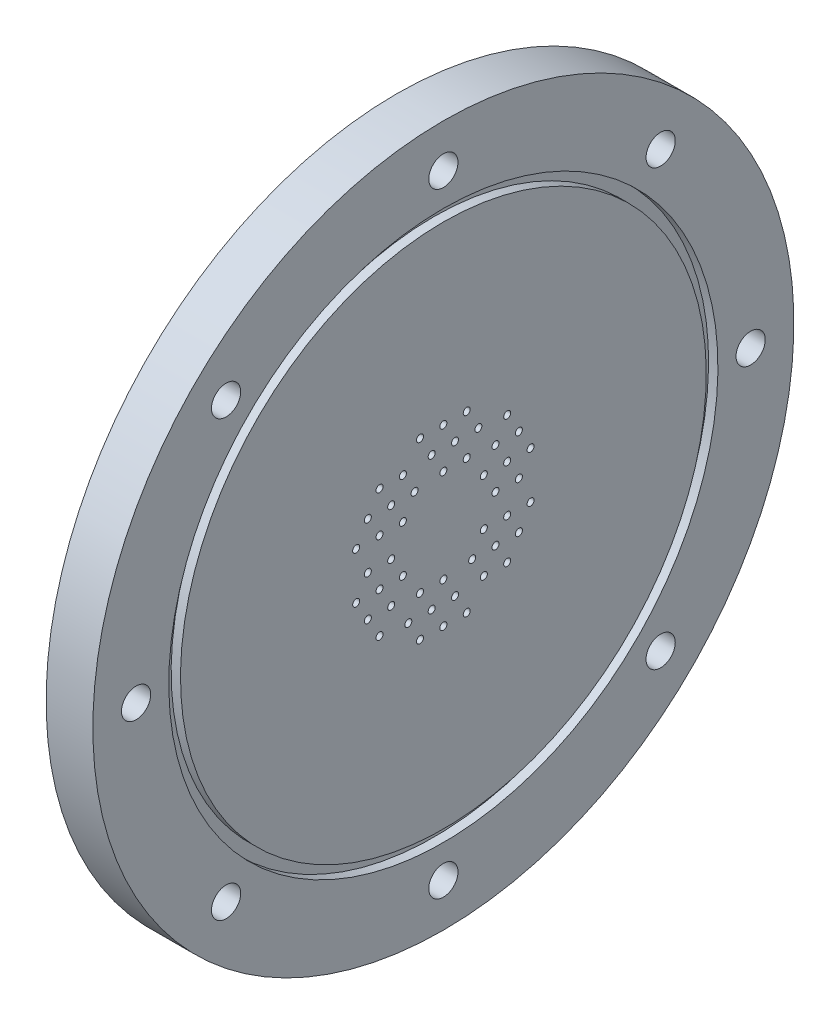
SolidWorks part; units mm, degrees
ref_plane "Front Plane" through (0, 0, 0) normal (0, 0, 1) x (1, 0, 0)
ref_plane "Top Plane" through (0, 0, 0) normal (0, 1, 0) x (1, 0, 0)
ref_plane "Right Plane" through (0, 0, 0) normal (1, 0, 0) x (0, 0, -1)
sketch "Sketch1" plane through (0, 0, 0) normal (0, 0, 1) x (1, 0, 0)
  line L0 (0, 0) -> (0, 48.26)
  line L1 (-2.54, 50.8) -> (-6.35, 50.8)
  line L2 (-6.35, 50.8) -> (-6.35, 76.2)
  line L3 (-6.35, 76.2) -> (3.81, 76.2)
  line L4 (3.81, 76.2) -> (3.81, 0)
  line L5 (3.81, 0) -> (0, 0)
  line L6 (-6.35, 50.8) -> (-6.35, 0) construction
  line L7 (-6.35, 0) -> (0, 0) construction
  arc A0 (0, 48.26) -> (-2.54, 50.8) centre (-2.54, 48.26) ccw
  dimension "Injector Plate Edge Curve" = 2.54
  dimension "Injector Plate Main Thickness" = 3.81
  dimension "Comp" = 152.4
  dimension "Injector Plate Boundry" = 25.4
  dimension "Injector Plate Manifold Height" = 6.35
revolve "Revolve1" add sketch "Sketch1" angle 360 about L7
sketch "Sketch2" plane through (3.81, 0, 0) normal (1, 0, 0) x (0, 0, -1)
  line L0 (0, 10.16) -> (5.08, 10.16) construction
  line L37 (5.08, 10.16) -> (2.54, 14.5594) construction
  line L38 (0, 10.16) -> (-2.54, 14.5594) construction
  line L39 (2.54, 14.5594) -> (0, 10.16) construction
  line L40 (-2.54, 14.5594) -> (2.54, 14.5594) construction
  line L41 (2.54, 14.5594) -> (7.62, 14.5594) construction
  line L42 (7.62, 14.5594) -> (5.08, 10.16) construction
  line L43 (2.54, 14.5594) -> (5.08, 18.9588) construction
  line L44 (5.08, 18.9588) -> (7.62, 14.5594) construction
  line L45 (-2.54, 14.5594) -> (0, 18.9588) construction
  line L46 (0, 18.9588) -> (2.54, 14.5594) construction
  line L47 (0, 18.9588) -> (5.08, 18.9588) construction
  line L48 (-2.54, 14.5594) -> (-5.08, 18.9588) construction
  line L49 (-5.08, 18.9588) -> (0, 18.9588) construction
  circle A3 centre (0, 10.16) radius 0.762
  circle A7 centre (-2.54, 14.5594) radius 0.762
  circle A8 centre (5.08, 10.16) radius 0.762
  circle A9 centre (-5.08, 18.9588) radius 0.762
  circle A10 centre (0, 18.9588) radius 0.762
  circle A11 centre (5.08, 18.9588) radius 0.762
  circle A12 centre (7.62, 14.5594) radius 0.762
  circle A13 centre (2.54, 14.5594) radius 0.762
  dimension "Injector Plate Holes Diameter" = 1.524
  dimension "Distance Between Holes" = 5.08
  dimension "1st Hole Distance from Center" = 10.16
extrude "Cut-Extrude1" cut sketch "Sketch2" against normal through all
chamfer "Chamfer1" distance 0.508 8 edges at (0, 10.922, 0) (0, 10.922, -5.08) (0, 15.3214, -7.62) (0, 15.3214, -2.54) (0, 15.3214, 2.54) (0, 19.7208, 5.08) (0, 19.7208, 0) (0, 19.7208, -5.08)
pattern_circular "CirPattern1" count 6 over 360 about axis through (0, 0, 0) along (1, 0, 0) of "Cut-Extrude1", "Chamfer1"
sketch "Sketch3" plane through (3.81, 0, 0) normal (1, 0, 0) x (0, 0, -1)
  line L0 (-66.802, 0) -> (0, 0) construction
  circle A0 centre (-66.802, 0) radius 3.175
  dimension "Screw Hole Diameter" = 6.35
  dimension "Injector Plate Screw Hole Distance" = 66.802
extrude "Cut-Extrude2" cut sketch "Sketch3" against normal through all
pattern_circular "CirPattern2" count 8 over 360 about axis through (0, 0, 0) along (1, 0, 0) of "Cut-Extrude2"
sketch "Sketch4" plane through (0, 0, 0) normal (0, 0, 1) x (1, 0, 0)
  line L0 (3.81, -76.2) -> (3.81, 76.2) construction
  line L1 (3.81, 59.69) -> (1.778, 59.69)
  line L2 (3.81, 59.69) -> (3.81, 57.15)
  line L3 (3.81, 57.15) -> (1.778, 57.15)
  line L4 (1.778, 59.69) -> (1.778, 57.15)
  line L5 (-6.35, 76.2) -> (-6.35, -76.2) construction
  line L6 (-6.35, 59.69) -> (-4.318, 59.69)
  line L7 (-6.35, 59.69) -> (-6.35, 57.15)
  line L8 (-6.35, 57.15) -> (-4.318, 57.15)
  line L9 (-4.318, 59.69) -> (-4.318, 57.15)
  line L11 (0, 0) -> (-6.35, 0) construction
  line L13 (-6.35, 50.8) -> (-5.08, 50.8)
  line L14 (-6.35, 50.8) -> (-6.35, 53.34)
  line L15 (-6.35, 53.34) -> (-5.08, 53.34)
  line L16 (-5.08, 50.8) -> (-5.08, 53.34)
  dimension "O-Ring Depth" = 2.032
  dimension "O-Ring Width" = 2.54
  dimension "Locater Ring Width" = 2.54
  dimension "Locater Ring Depth" = 1.27
  dimension "O-Ring Radius" = 57.15
revolve "Cut-Revolve1" cut sketch "Sketch4" angle 360 about L11
